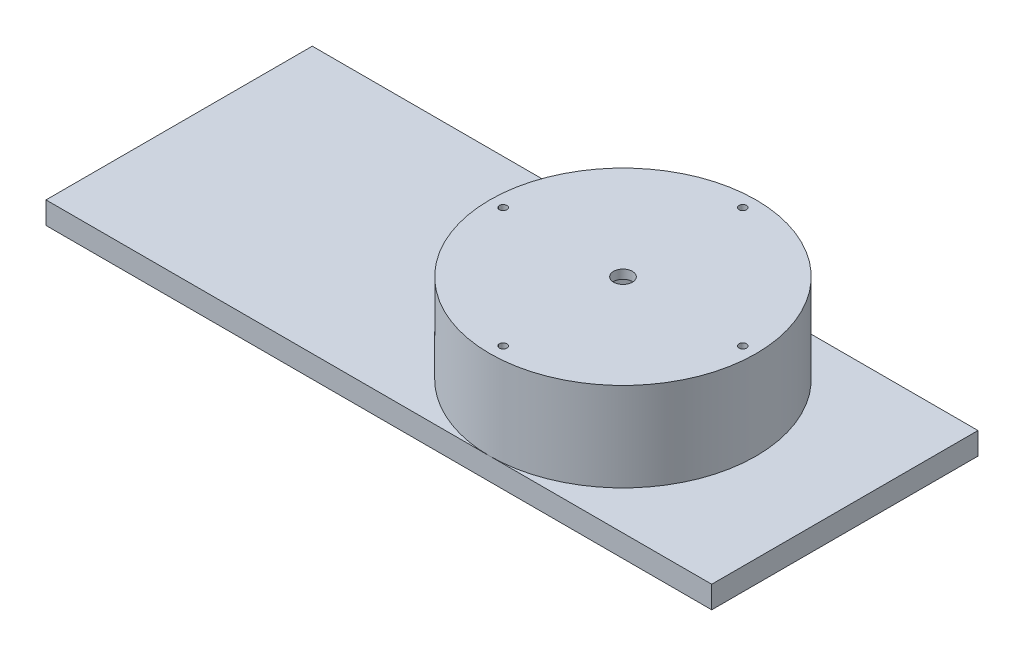
SolidWorks part; units mm, degrees
ref_plane "Piano frontale" through (0, 0, 0) normal (0, 0, 1) x (1, 0, 0)
ref_plane "Piano superiore" through (0, 0, 0) normal (0, 1, 0) x (1, 0, 0)
ref_plane "Piano destro" through (0, 0, 0) normal (1, 0, 0) x (0, 0, -1)
sketch "Schizzo1" plane through (0, 0, 0) normal (0, 1, 0) x (1, 0, 0)
  line L1 (0, 0) -> (-300, 0)
  line L2 (0, 0) -> (0, 120)
  line L3 (0, 120) -> (-300, 120)
  line L4 (-300, 0) -> (-300, 120)
  dimension "D1" = 300
  dimension "D2" = 120
extrude "Estrusione-Estrusione1" add sketch "Schizzo1" along normal blind 10
sketch "Schizzo4" plane through (0, 10, 0) normal (0, 1, 0) x (1, 0, 0)
  line L0 (-300, 120) -> (-300, 0) construction
  line L2 (-300, 0) -> (0, 0) construction
  circle A0 centre (-100, 60) radius 60
  dimension "D1" = 200
  dimension "D3" = 120
  dimension "D2" = 60
extrude "Estrusione-Estrusione2" add sketch "Schizzo4" along normal blind 40
sketch "Schizzo5" plane through (0, 0, 0) normal (0, -1, 0) x (1, 0, 0)
  line L0 (0, -120) -> (-300, -120) construction
  line L1 (-300, -120) -> (-300, 0) construction
  circle A0 centre (-100, -60) radius 48
  dimension "D1" = 96
  dimension "D3" = 200
  dimension "D2" = 60
extrude "Taglio-Estrusione1" cut sketch "Schizzo5" against normal blind 46
sketch "Schizzo6" plane through (0, 46, 0) normal (0, -1, 0) x (1, 0, 0)
  line L0 (0, -120) -> (-300, -120) construction
  line L1 (-300, -120) -> (-300, 0) construction
  circle A0 centre (-100, -60) radius 4.25
  dimension "D1" = 8.5
  dimension "D2" = 60
  dimension "D3" = 200
extrude "Taglio-Estrusione2" cut sketch "Schizzo6" against normal blind 46
ref_plane "Piano1" through (-160, 0, 0) normal (-1, 0, 0) x (0, 0, 1)
sketch "Schizzo7" plane through (-160, 0, 0) normal (-1, 0, 0) x (0, 0, 1)
  line L0 (-120, 10) -> (0, 10) construction
  line L1 (-70, 10) -> (-50, 10)
  line L2 (-70, 10) -> (-70, 12)
  line L3 (-70, 12) -> (-50, 12)
  line L4 (-50, 10) -> (-50, 12)
  line L5 (-120, 10) -> (-120, 0) construction
  dimension "D1" = 20
  dimension "D2" = 2
  dimension "D3" = 50
extrude "Taglio-Estrusione3" cut sketch "Schizzo7" against normal blind 46 contours L1 L4 L3 L2
sketch "Schizzo2" plane through (0, 50, 0) normal (0, 1, 0) x (1, 0, 0)
  line L0 (-300, 60) -> (-100, 60) construction
  line L1 (-300, 120) -> (-300, 0) construction
  circle A0 centre (-100, 60) radius 54 construction
  point P6 (-100, 114)
  point P8 (-46, 60)
  point P10 (-100, 6)
  point P12 (-154, 60)
  dimension "D2" = 108
  dimension "D1" = 200
hole_wizard "Foro per Vite M3-1" positions "Schizzo2" profile "Schizzo3" hole size "M3" standard "ISO"
sketch "Schizzo3" plane through (-154, 50, -60) normal (1, 0, 0) x (0, 0, 1)
  line L0 (0, 0) -> (0, 6.0215)
  line L1 (0, 6.0215) -> (1.7, 5)
  line L2 (1.7, 5) -> (1.7, 0)
  line L5 (1.7, 0) -> (0, 0)
  line L10 (0, 6.0215) -> (-1.7, 5) construction
  line L11 (0, -6.35) -> (0, 107.95) construction
  dimension "Hole Dia." = 3.4
  dimension "Hole Depth" = 5
  dimension "Drill Angle" = 118
